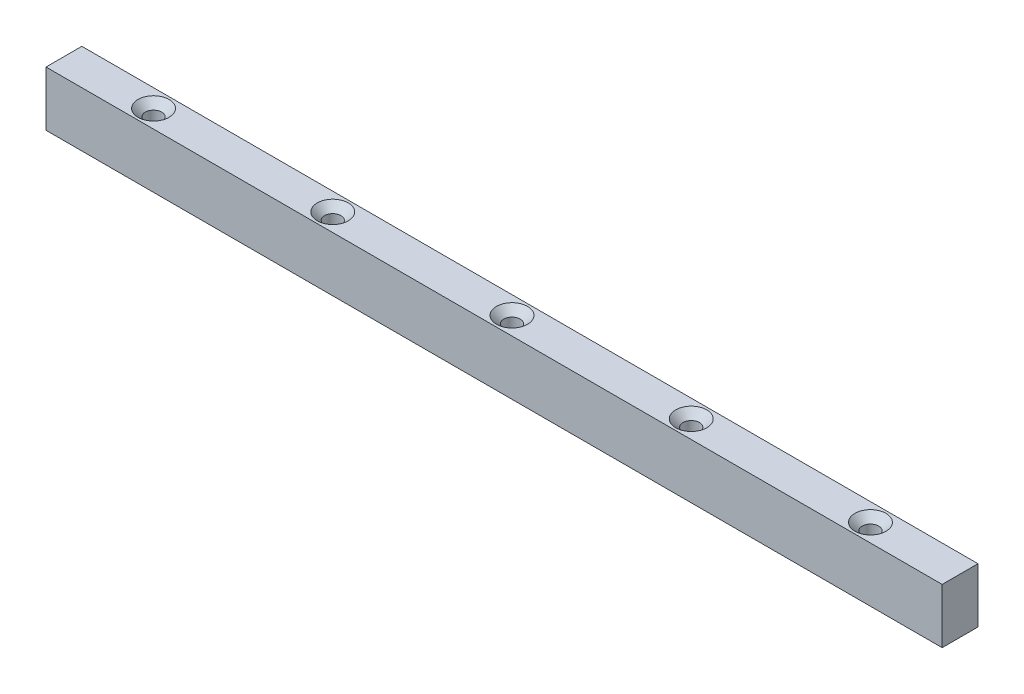
SolidWorks part; units mm, degrees
material "3.1355 (EN-AW 2024)"
ref_plane "Спереди" through (0, 0, 0) normal (0, 0, 1) x (1, 0, 0)
ref_plane "Сверху" through (0, 0, 0) normal (0, 1, 0) x (1, 0, 0)
ref_plane "Справа" through (0, 0, 0) normal (1, 0, 0) x (0, 0, -1)
sketch "Эскиз1" plane through (0, 0, 0) normal (0, 1, 0) x (1, 0, 0)
  line L1 (-150, 12) -> (150, 12)
  line L2 (-150, 12) -> (-150, 0)
  line L3 (-150, 0) -> (150, 0)
  line L4 (150, 12) -> (150, 0)
  point P4 (0, 0)
  dimension "D1" = 300
  dimension "D2" = 12
extrude "База" add sketch "Эскиз1" along normal blind 18.35
hole_wizard "Крепление-M4" positions "Эскиз3" profile "Эскиз4" countersink size "M5" standard "DIN" end condition through all
sketch "Эскиз3" plane through (0, 18.35, 0) normal (0, -1, 0) x (-1, 0, 0)
  line L0 (0, 6) -> (0, 0) construction
  line L4 (0, 6) -> (0, 12) construction
  line L5 (-150, 12) -> (150, 12) construction
  point P0 (0, 6)
sketch "Эскиз4" plane through (0, 18.35, -6) normal (1, 0, 0) x (0, 0, 1)
  line L0 (0, 0) -> (0, 18.35)
  line L1 (0, 18.35) -> (2.75, 18.35)
  line L2 (2.75, 18.35) -> (2.75, 2.45)
  line L3 (2.75, 2.45) -> (5.2, 0)
  line L5 (5.2, 0) -> (0, 0)
  line L6 (-2.75, 2.45) -> (-5.2, 0) construction
  line L11 (0, -6.35) -> (0, 107.95) construction
  dimension "Диаметр сквозного отверстия" = 5.5
  dimension "Глубина сквозного отверстия" = 18.35
  dimension "Диаметр передней зенковки" = 10.4
  dimension "Угол передней зенковки" = 90
pattern_linear "Линейный массив1" count 3 spacing 60 along (-1, 0, 0) count 3 spacing 60 along (1, 0, 0) of "Крепление-M4"
sketch "Эскиз5" plane through (0, 0, -12) normal (0, 0, 1) x (1, 0, 0)
  line L0 (-150, 18.35) -> (-150, 0) construction
  line L1 (-144, 9.175) -> (-150, 9.175) construction
  line L2 (144, 9.175) -> (150, 9.175) construction
  line L3 (150, 18.35) -> (150, 0) construction
  circle A0 centre (-144, 9.175) radius 3
  circle A1 centre (144, 9.175) radius 3
  point P6 (-150, 9.175)
  dimension "D1" = 6
  dimension "D2" = 6
extrude "Валы-6мм" cut sketch "Эскиз5" along normal blind 11
